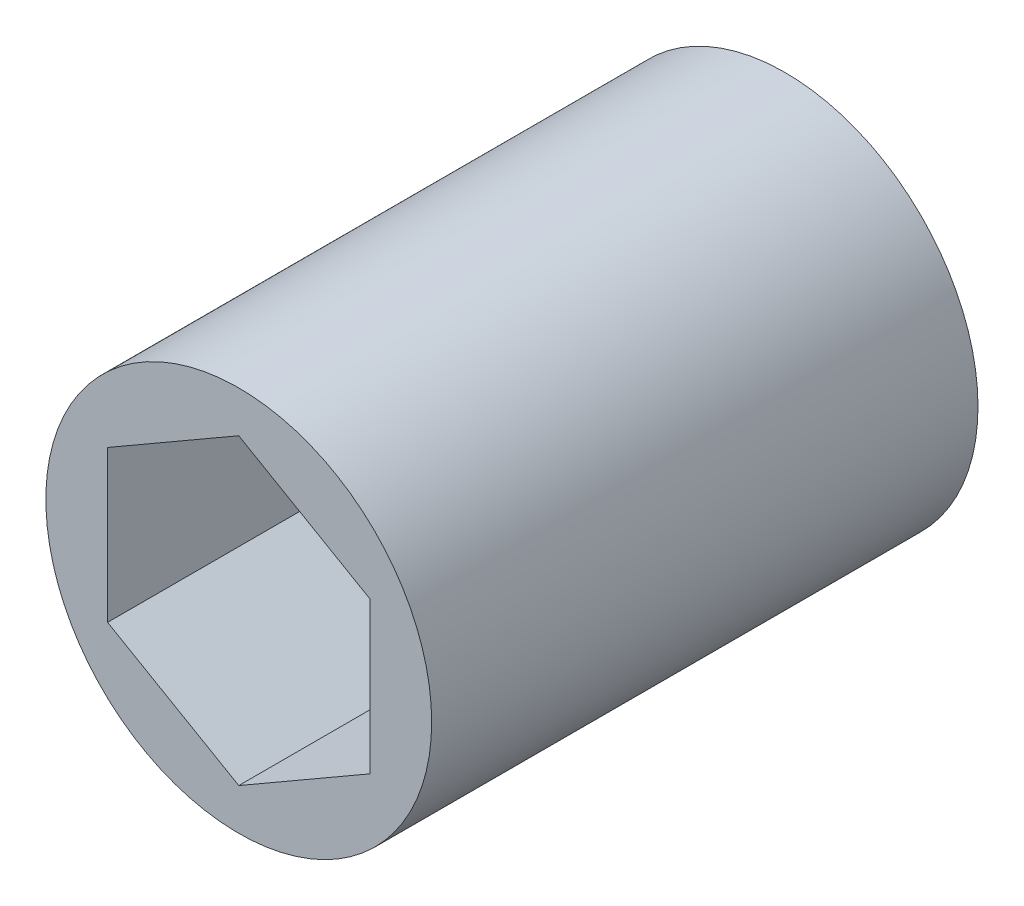
SolidWorks part; units mm, degrees
material "PET"
ref_plane "Front Plane" through (0, 0, 0) normal (0, 0, 1) x (1, 0, 0)
ref_plane "Top Plane" through (0, 0, 0) normal (0, 1, 0) x (1, 0, 0)
ref_plane "Right Plane" through (0, 0, 0) normal (1, 0, 0) x (0, 0, -1)
sketch "Sketch1" plane through (0, 0, 0) normal (0, 0, 1) x (1, 0, 0)
  line L1 (0, 7.479) -> (-6.477, 3.7395)
  line L2 (-6.477, 3.7395) -> (-6.477, -3.7395)
  line L3 (-6.477, -3.7395) -> (0, -7.479)
  line L4 (0, -7.479) -> (6.477, -3.7395)
  line L5 (6.477, -3.7395) -> (6.477, 3.7395)
  line L6 (6.477, 3.7395) -> (0, 7.479)
  circle A0 centre (0, 0) radius 9.525
  circle A1 centre (0, 0) radius 6.477 construction
  dimension "D1" = 12.954
  dimension "D2" = 19.05
extrude "Boss-Extrude1" add sketch "Sketch1" along normal mid plane 26.9748
